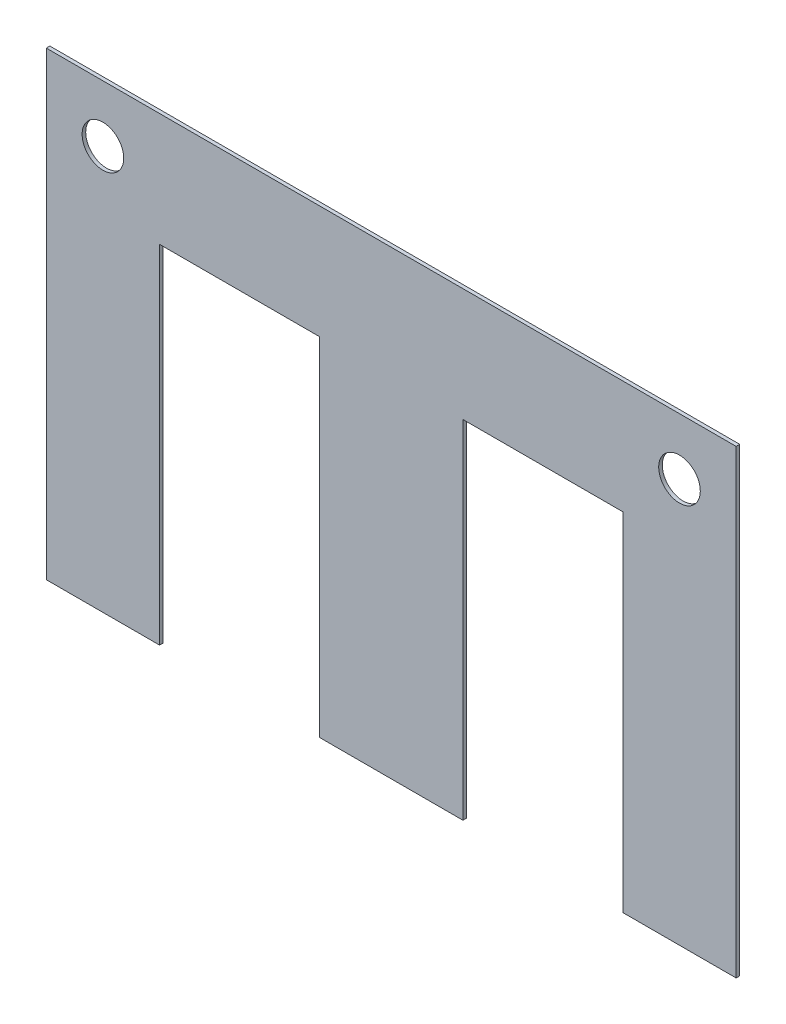
SolidWorks part; units mm, degrees
ref_plane "Front Plane" through (0, 0, 0) normal (0, 0, 1) x (1, 0, 0)
ref_plane "Top Plane" through (0, 0, 0) normal (0, 1, 0) x (1, 0, 0)
ref_plane "Right Plane" through (0, 0, 0) normal (1, 0, 0) x (0, 0, -1)
sketch "Sketch1" plane through (0, 0, 0) normal (0, 0, 1) x (1, 0, 0)
  line L1 (-48.1, 32.1) -> (48.1, 32.1)
  line L2 (48.1, 32.1) -> (48.1, -32.1)
  line L3 (48.1, -32.1) -> (32.3, -32.1)
  line L4 (32.3, 16.3) -> (10, 16.3)
  line L5 (32.3, -32.1) -> (32.3, 16.3)
  line L7 (10, 16.3) -> (10, -32.1)
  line L8 (-10, -32.1) -> (10, -32.1)
  line L10 (-10, 16.3) -> (-32.3, 16.3)
  line L11 (-48.1, -32.1) -> (-32.3, -32.1)
  line L12 (-48.1, 32.1) -> (-48.1, -32.1)
  line L13 (-32.3, -32.1) -> (-32.3, 16.3)
  line L15 (-10, 16.3) -> (-10, -32.1)
  line L16 (32.3, 16.3) -> (10, 16.3) construction
  line L17 (-10, 16.3) -> (-32.3, 16.3) construction
  circle A0 centre (40.2, 24.2) radius 2.9
  circle A1 centre (-40.2, 24.2) radius 2.9
  point P4 (0, 0)
  point P7 (0, 32.1)
  point P14 (0, 16.3)
  point P20 (0, -32.1)
  dimension "D2" = 96.2
extrude "Boss-Extrude1" add sketch "Sketch1" along normal mid plane 0.5
